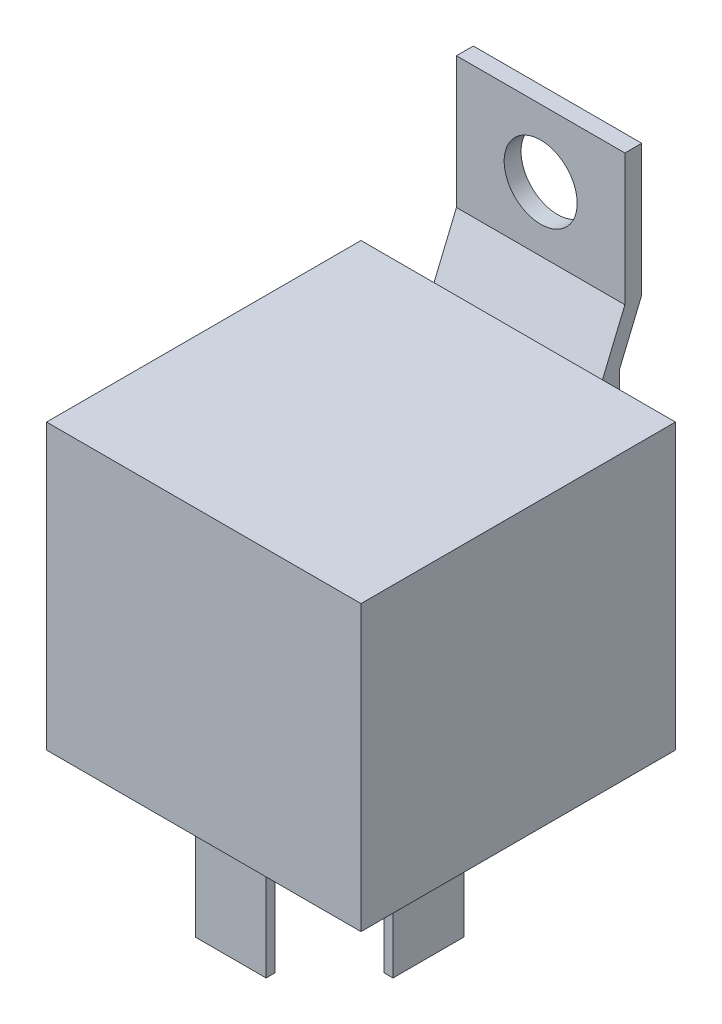
SolidWorks part; units mm, degrees
ref_plane "Plan de face" through (0, 0, 0) normal (0, 0, 1) x (1, 0, 0)
ref_plane "Plan de dessus" through (0, 0, 0) normal (0, 1, 0) x (1, 0, 0)
ref_plane "Plan de droite" through (0, 0, 0) normal (1, 0, 0) x (0, 0, -1)
sketch "Esquisse1" plane through (0, 0, 0) normal (0, 0, 1) x (1, 0, 0)
  line L1 (-14, 12.65) -> (14, 12.65)
  line L2 (-14, 12.65) -> (-14, -12.65)
  line L3 (-14, -12.65) -> (14, -12.65)
  line L4 (14, 12.65) -> (14, -12.65)
  point P4 (0, 12.65)
  point P6 (-14, 0)
  dimension "D1" = 28
  dimension "D2" = 25.3
extrude "Boss.-Extru.1" add sketch "Esquisse1" along normal blind 28
sketch "Esquisse2" plane through (0, 0, 0) normal (1, 0, 0) x (0, 0, -1)
  line L0 (0, 12.65) -> (2, 17.4465)
  line L1 (2, 17.4465) -> (2, 29.15)
  line L2 (2, 29.15) -> (3.5, 29.15)
  line L3 (3.5, 29.15) -> (3.5, 17.4465)
  line L4 (3.5, 17.4465) -> (1.5, 12.65)
  line L5 (1.5, 12.65) -> (1.5, -3.0739)
  line L6 (1.5, -3.0739) -> (0, -3.0739)
  line L7 (0, -3.0739) -> (0, 12.65)
  line L8 (0, -12.65) -> (0, 12.65) construction
  line L9 (-28, 12.65) -> (0, 12.65) construction
  dimension "D1" = 16.5
  dimension "D2" = 3.5
  dimension "D3" = 1.5
extrude "Boss.-Extru.2" add sketch "Esquisse2" along normal mid plane 15
sketch "Esquisse3" plane through (0, 0, -2) normal (0, 0, 1) x (1, 0, 0)
  line L0 (7.5, 29.15) -> (-7.5, 29.15) construction
  circle A0 centre (0, 23.15) radius 3.25
  dimension "D2" = 6.5
  dimension "D1" = 6
extrude "Enlèv. mat.-Extru.1" cut sketch "Esquisse3" against normal through all
sketch "Esquisse4" plane through (0, -12.65, 0) normal (0, -1, 0) x (1, 0, 0)
  line L0 (0, 0) -> (0, 28) construction
  line L5 (-14, 0) -> (14, 0) construction
  line L6 (-14, 28) -> (14, 28) construction
  line L7 (8.8, 13.65) -> (8, 13.65)
  line L8 (-0.4, 10.45) -> (0.4, 10.45)
  line L9 (-0.4, 10.45) -> (-0.4, 4.15)
  line L10 (-0.4, 4.15) -> (0.4, 4.15)
  line L11 (0.4, 10.45) -> (0.4, 4.15)
  line L12 (-3.15, 25.6) -> (3.15, 25.6)
  line L13 (-3.15, 25.6) -> (-3.15, 24.8)
  line L14 (-3.15, 24.8) -> (3.15, 24.8)
  line L15 (3.15, 25.6) -> (3.15, 24.8)
  line L16 (-8.8, 19.95) -> (-8, 19.95)
  line L17 (-8.8, 19.95) -> (-8.8, 13.65)
  line L18 (-8.8, 13.65) -> (-8, 13.65)
  line L19 (-8, 19.95) -> (-8, 13.65)
  line L20 (-3.15, 17.6) -> (3.15, 17.6)
  line L21 (-3.15, 17.6) -> (-3.15, 16.8)
  line L22 (-3.15, 16.8) -> (3.15, 16.8)
  line L23 (3.15, 17.6) -> (3.15, 16.8)
  line L24 (8, 19.95) -> (8, 13.65)
  line L25 (8.8, 19.95) -> (8.8, 13.65)
  line L26 (8.8, 19.95) -> (8, 19.95)
  point P15 (0, 25.6)
  point P16 (0, 10.45)
  point P25 (0, 17.6)
  point P30 (-3.15, 17.2)
  point P31 (-3.15, 25.2)
  point P32 (0.4, 7.3)
  point P33 (3.15, 25.2)
  point P34 (8.8, 16.8)
  point P35 (8.4, 13.65)
  point P36 (-8.4, 13.65)
  dimension "D1" = 0.8
  dimension "D2" = 6.3
  dimension "D3" = 8
  dimension "D4" = 2.8
  dimension "D5" = 17.9
  dimension "D6" = 8.4
  dimension "D7" = 16.8
extrude "Boss.-Extru.3" add sketch "Esquisse4" along normal blind 10.2
